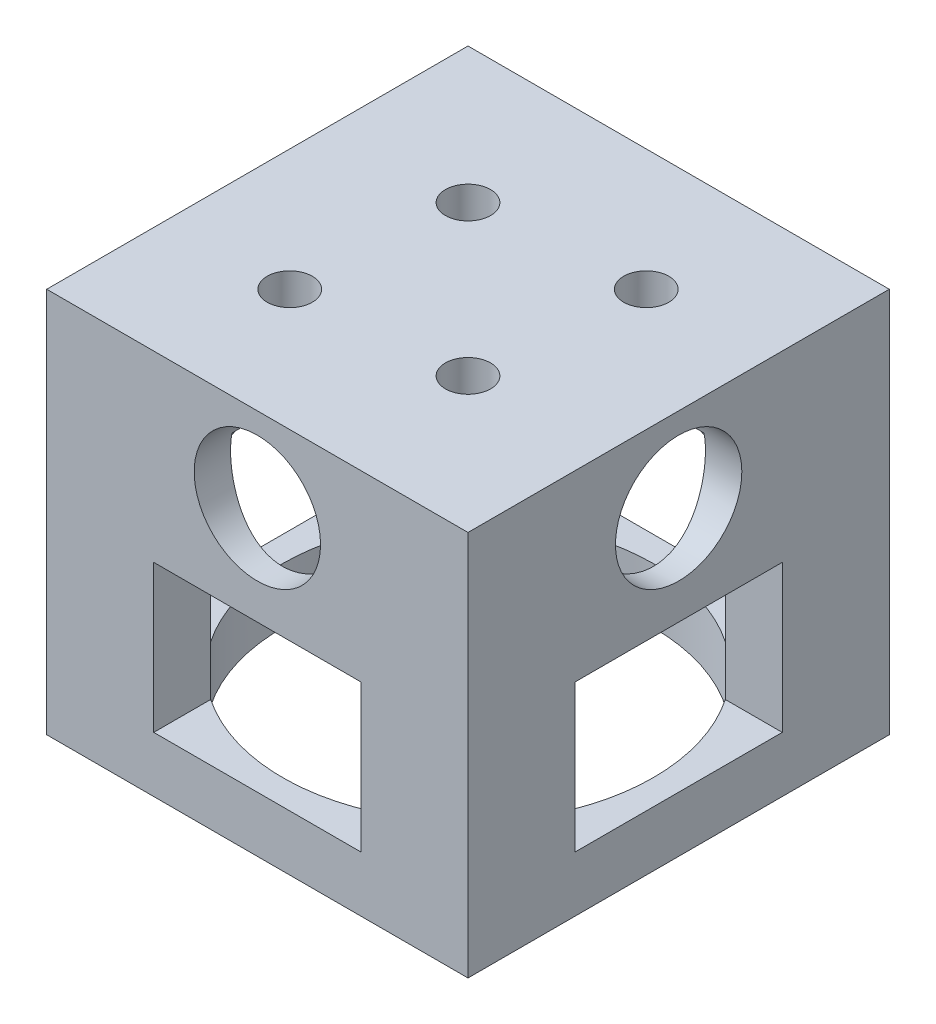
SolidWorks part; units mm, degrees
ref_plane "Front Plane" through (0, 0, 0) normal (0, 0, 1) x (1, 0, 0)
ref_plane "Top Plane" through (0, 0, 0) normal (0, 1, 0) x (1, 0, 0)
ref_plane "Right Plane" through (0, 0, 0) normal (1, 0, 0) x (0, 0, -1)
sketch "Sketch1" plane through (0, 0, 0) normal (0, 1, 0) x (1, 0, 0)
  line L0 (-55, 0) -> (55, 0) construction
  line L1 (-15.875, -15.875) -> (15.875, -15.875)
  line L2 (-15.875, -15.875) -> (-15.875, 15.875)
  line L3 (-15.875, 15.875) -> (15.875, 15.875)
  line L4 (15.875, -15.875) -> (15.875, 15.875)
  line L5 (-15.875, -15.875) -> (15.875, 15.875) construction
  line L6 (-15.875, 15.875) -> (15.875, -15.875) construction
  line L7 (-6.7175, -6.7175) -> (6.7175, 6.7175) construction
  line L8 (-5.6569, 5.6569) -> (5.6569, -5.6569) construction
  point P0 (0, 0)
  point P6 (-5.6569, 5.6569)
  point P7 (5.6569, -5.6569)
  point P8 (-6.7175, -6.7175)
  point P9 (6.7175, 6.7175)
  point P14 (0, 0)
  point P17 (0, 0)
  dimension "D1" = 19
  dimension "D2" = 16
  dimension "D3" = 45
  dimension "D4" = 31.75
extrude "Boss-Extrude1" add sketch "Sketch1" along normal blind 5.08
sketch "Sketch4" plane through (0, 5.08, 0) normal (0, 1, 0) x (1, 0, 0)
  point P0 (5.6569, -5.6569)
  point P2 (-6.7175, -6.7175)
  point P4 (6.7175, 6.7175)
  point P6 (-5.6569, 5.6569)
hole_wizard "M3 Clearance Hole1" positions "Sketch5" profile "Sketch6" hole size "M3" standard "ANSI Metric"
sketch "Sketch5" plane through (0, 5.08, 0) normal (0, 1, 0) x (1, 0, 0)
  point P0 (-5.6569, 5.6569)
  point P3 (6.7175, 6.7175)
  point P6 (5.6569, -5.6569)
  point P9 (-6.7175, -6.7175)
sketch "Sketch6" plane through (-5.6569, 5.08, -5.6569) normal (1, 0, 0) x (0, 0, 1)
  line L0 (0, 0) -> (0, 16.2615)
  line L1 (0, 16.2615) -> (1.7, 15.24)
  line L2 (1.7, 15.24) -> (1.7, 0)
  line L5 (1.7, 0) -> (0, 0)
  line L10 (0, 16.2615) -> (-1.7, 15.24) construction
  line L11 (0, -6.35) -> (0, 107.95) construction
  dimension "Hole Dia." = 3.4
  dimension "Hole Depth" = 15.24
  dimension "Drill Angle" = 118
sketch "Sketch7" plane through (0, 0, 0) normal (0, -1, 0) x (1, 0, 0)
  line L0 (15.875, -15.875) -> (-15.875, -15.875) construction
  line L1 (-15.875, -15.875) -> (-15.875, 15.875) construction
  line L2 (15.875, 15.875) -> (15.875, -15.875) construction
  line L3 (-15.875, 15.875) -> (15.875, 15.875) construction
  line L4 (15.875, -15.875) -> (-15.875, -15.875)
  line L5 (-15.875, -15.875) -> (-15.875, 15.875)
  line L6 (15.875, 15.875) -> (15.875, -15.875)
  line L7 (-15.875, 15.875) -> (15.875, 15.875)
  circle A0 centre (0, 0) radius 13.97
  dimension "D1" = 27.94
extrude "Boss-Extrude2" add sketch "Sketch7" along normal blind 24
sketch "Sketch8" plane through (0, -24, 0) normal (0, -1, 0) x (1, 0, 0)
  line L0 (-15.875, -15.875) -> (15.875, -15.875) construction
  line L1 (15.875, -15.875) -> (15.875, 15.875) construction
  line L2 (12.7, -12.7) -> (-12.7, -12.7) construction
  line L3 (-12.7, -12.7) -> (-12.7, 12.7) construction
  line L4 (0, -15.994) -> (0, 15.994) construction
  line L5 (15.994, 0) -> (-15.994, 0) construction
  point P0 (12.7, -12.7)
  point P1 (-12.7, -12.7)
  point P2 (12.7, 12.7)
  point P3 (-12.7, 12.7)
  point P4 (0, -12.7)
  point P14 (-12.7, 0)
  dimension "D1" = 3.175
  dimension "D2" = 3.175
hole_wizard "M3x0.5 Tapped Hole1" positions "Sketch9" profile "Sketch11" tap size "M3x0.5" standard "ANSI Metric"
sketch "Sketch9" plane through (0, -24, 0) normal (0, -1, 0) x (-1, 0, 0)
  point P0 (-12.7, 12.7)
  point P3 (12.7, 12.7)
  point P6 (12.7, -12.7)
  point P9 (-12.7, -12.7)
sketch "Sketch11" plane through (12.7, -24, -12.7) normal (1, 0, 0) x (0, 0, -1)
  line L0 (0, 0) -> (0, 15.9911)
  line L1 (0, 15.9911) -> (1.25, 15.24)
  line L2 (1.25, 15.24) -> (1.25, 0)
  line L5 (1.25, 0) -> (0, 0)
  line L10 (0, 15.9911) -> (-1.25, 15.24) construction
  line L11 (0, -6.35) -> (0, 107.95) construction
  dimension "Tap Drill Dia." = 2.5
  dimension "Tap Drill Depth" = 15.24
  dimension "Drill Angle" = 118
cosmetic thread "Hole Thread1" parameters "D1"=6.096, "D2"=3
cosmetic thread "Hole Thread2" parameters "D1"=6.096, "D2"=3
cosmetic thread "Hole Thread3" parameters "D1"=6.096, "D2"=3
cosmetic thread "Hole Thread4" parameters "D1"=6.096, "D2"=3
sketch "Sketch12" plane through (0, 0, -15.875) normal (0, 0, -1) x (-1, 0, 0)
  line L0 (0, 15.994) -> (0, -15.994) construction
  line L1 (-15.875, 5.08) -> (15.875, 5.08) construction
  circle A0 centre (0, -1.27) radius 4.7625
  dimension "D2" = 9.525
  dimension "D1" = 6.35
extrude "Cut-Extrude1" cut sketch "Sketch12" against normal blind 6.35
sketch "Sketch13" plane through (0, 0, -15.875) normal (0, 0, -1) x (-1, 0, 0)
  line L0 (0, 15.994) -> (0, -15.994) construction
  line L1 (-7.8095, -19.8109) -> (7.8095, -19.8109)
  line L2 (-7.8095, -19.8109) -> (-7.8095, -8.7122)
  line L3 (-7.8095, -8.7122) -> (7.8095, -8.7122)
  line L4 (7.8095, -19.8109) -> (7.8095, -8.7122)
  line L5 (-7.8095, -19.8109) -> (7.8095, -8.7122) construction
  line L6 (-7.8095, -8.7122) -> (7.8095, -19.8109) construction
  point P0 (0, -14.2615)
  point P7 (0, -14.2086)
  point P8 (-7.8095, -8.7122)
extrude "Cut-Extrude2" cut sketch "Sketch13" against normal up to next
pattern_circular "CirPattern1" count 4 over 360 about axis through (0, 0, 0) along (0, 1, 0) of "Cut-Extrude2"
pattern_circular "CirPattern2" count 4 over 360 about axis through (0, 0, 0) along (0, 1, 0) of "Cut-Extrude1"
